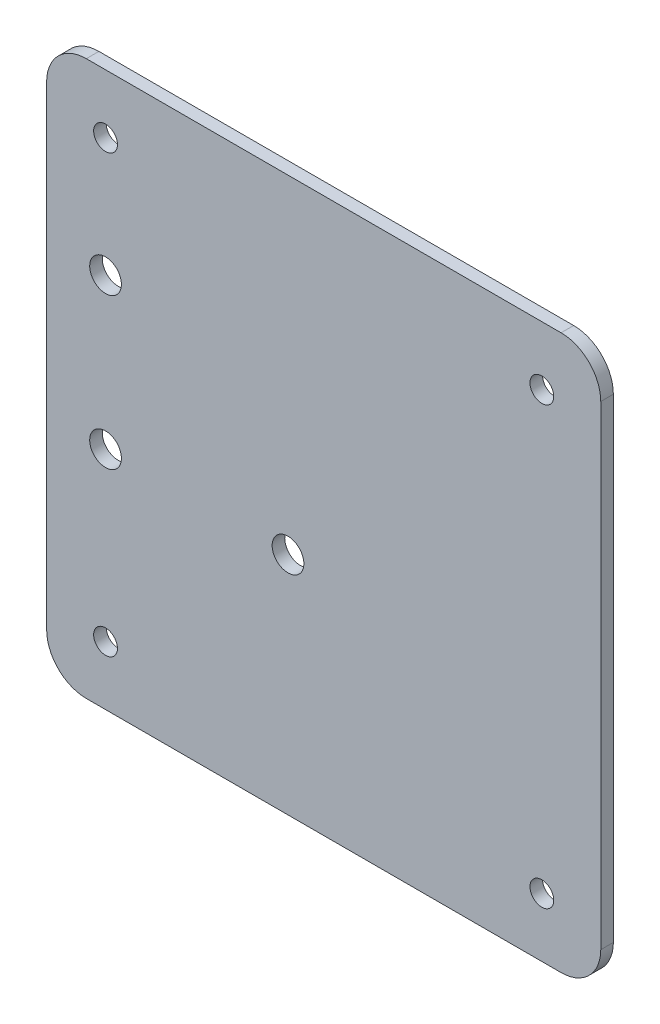
SolidWorks part; units mm, degrees
ref_plane "Front Plane" through (0, 0, 0) normal (0, 0, 1) x (1, 0, 0)
ref_plane "Top Plane" through (0, 0, 0) normal (0, 1, 0) x (1, 0, 0)
ref_plane "Right Plane" through (0, 0, 0) normal (1, 0, 0) x (0, 0, -1)
sketch "Sketch1" plane through (0, 0, 0) normal (0, 0, 1) x (1, 0, 0)
  line L0 (56.6353, 1643.8233) -> (56.6353, 1636.7815) construction
  line L1 (66.6353, 1721.56) -> (186.3353, 1721.56)
  line L2 (56.6353, 1711.56) -> (56.6353, 1591.86)
  line L3 (66.6353, 1581.86) -> (186.3353, 1581.86)
  line L4 (196.3353, 1711.56) -> (196.3353, 1591.86)
  line L5 (-97.883, 1661.0458) -> (174.117, 1661.0458) construction
  arc A0 (56.6353, 1591.86) -> (66.6353, 1581.86) centre (66.6353, 1591.86) ccw
  arc A1 (186.3353, 1581.86) -> (196.3353, 1591.86) centre (186.3353, 1591.86) ccw
  arc A2 (186.3353, 1721.56) -> (196.3353, 1711.56) centre (186.3353, 1711.56) cw
  arc A3 (66.6353, 1721.56) -> (56.6353, 1711.56) centre (66.6353, 1711.56) ccw
  point P10 (56.6353, 1581.86)
  point P13 (196.3353, 1581.86)
  dimension "D2" = 10
  dimension "D1" = 139.7
  dimension "D4" = 35
extrude "Boss-Extrude1" add sketch "Sketch1" along normal blind 3.175
sketch "Sketch2" plane through (0, 0, 0) normal (0, 0, -1) x (-1, 0, 0)
  line L0 (-71.4853, 1626.1374) -> (-71.4853, 1679.6302) construction
  line L1 (-117.4853, 1626.1374) -> (-117.4853, 1673.5664) construction
  line L2 (-71.4853, 1638.71) -> (-117.4853, 1638.71) construction
  line L3 (97.883, 1661.0458) -> (-207.117, 1661.0458) construction
  line L4 (-207.117, 1669.0458) -> (-207.117, 1653.0458) construction
  line L13 (-196.3353, 1651.71) -> (-56.6353, 1651.71) construction
  line L14 (-196.3353, 1591.86) -> (-196.3353, 1711.56) construction
  line L15 (-56.6353, 1711.56) -> (-56.6353, 1591.86) construction
  line L16 (-186.3353, 1721.56) -> (-66.6353, 1721.56) construction
  line L21 (-71.4853, 1596.71) -> (-71.4853, 1706.71) construction
  line L22 (-181.4853, 1596.71) -> (-71.4853, 1596.71) construction
  line L23 (-181.4853, 1706.71) -> (-181.4853, 1596.71) construction
  line L24 (-71.4853, 1706.71) -> (-181.4853, 1706.71) construction
  line L25 (-126.4853, 1721.56) -> (-126.4853, 1581.86) construction
  line L26 (-66.6353, 1581.86) -> (-186.3353, 1581.86) construction
  circle A3 centre (-71.4853, 1638.71) radius 4
  circle A4 centre (-71.4853, 1676.71) radius 4
  circle A5 centre (-117.4853, 1638.71) radius 4
  circle A6 centre (-181.4853, 1706.71) radius 3
  circle A7 centre (-71.4853, 1706.71) radius 3
  circle A8 centre (-181.4853, 1596.71) radius 3
  circle A9 centre (-71.4853, 1596.71) radius 3
  dimension "D1" = 8
  dimension "D3" = 6
  dimension "D4" = 15.6642
  dimension "D5" = 22.3358
  dimension "D6" = 9
  dimension "D7" = 46
  dimension "D8" = 55
  dimension "D2" = 55
  dimension "D9" = 55
  dimension "D10" = 55
extrude "Cut-Extrude1" cut sketch "Sketch2" against normal through all
